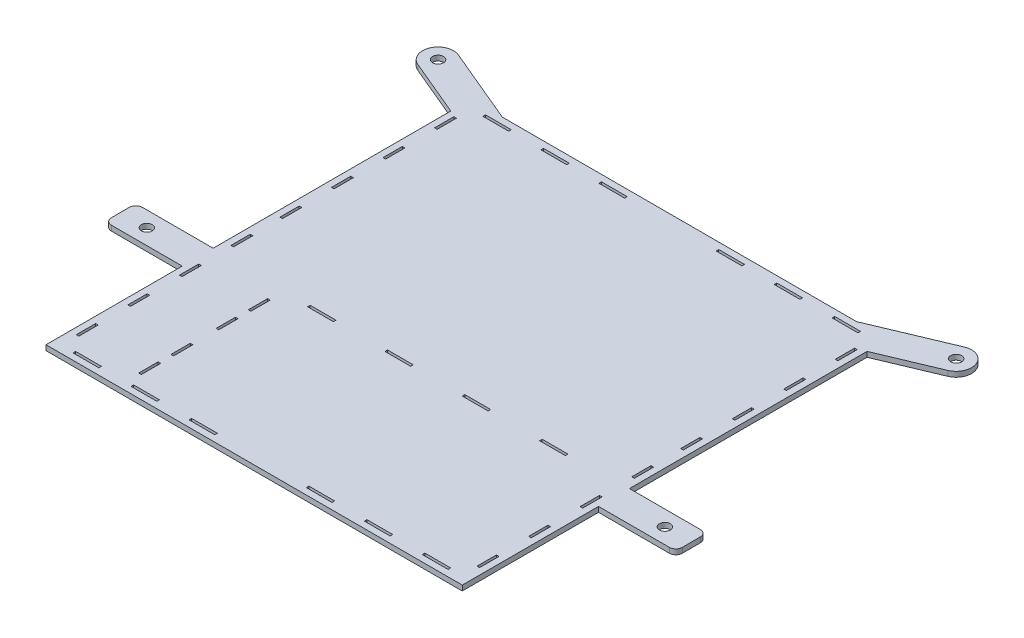
SolidWorks part; units mm, degrees
ref_plane "Front Plane" through (0, 0, 0) normal (0, 0, 1) x (1, 0, 0)
ref_plane "Top Plane" through (0, 0, 0) normal (0, 1, 0) x (1, 0, 0)
ref_plane "Right Plane" through (0, 0, 0) normal (1, 0, 0) x (0, 0, -1)
sketch "Sketch1" plane through (0, 0, 0) normal (0, 1, 0) x (1, 0, 0)
  line L0 (154.5, 106.5) -> (156.5, 106.5)
  line L1 (-161.5, -165) -> (161.5, -165)
  line L2 (-161.5, -165) -> (-161.5, -59.29)
  line L3 (-137.4311, 165) -> (137.4311, 165)
  line L4 (161.5, -165) -> (161.5, -59.29)
  line L5 (-161.5, -165) -> (161.5, 165) construction
  line L6 (-161.5, 165) -> (161.5, -165) construction
  line L7 (-155.5, -159) -> (155.5, -159) construction
  line L8 (-155.5, -159) -> (-155.5, 159) construction
  line L9 (-155.5, 159) -> (155.5, 159) construction
  line L10 (155.5, -159) -> (155.5, 159) construction
  line L11 (-155.5, -159) -> (155.5, 159) construction
  line L12 (-155.5, 159) -> (155.5, -159) construction
  line L13 (154.5, 146.5) -> (156.5, 146.5)
  line L14 (154.5, 146.5) -> (154.5, 131.5)
  line L15 (154.5, 131.5) -> (156.5, 131.5)
  line L16 (156.5, 146.5) -> (156.5, 131.5)
  line L17 (154.5, 146.5) -> (156.5, 131.5) construction
  line L18 (154.5, 131.5) -> (156.5, 146.5) construction
  line L19 (154.5, 106.5) -> (154.5, 91.5)
  line L20 (156.5, 106.5) -> (156.5, 91.5)
  line L21 (154.5, 91.5) -> (156.5, 91.5)
  line L22 (154.5, 106.5) -> (156.5, 91.5) construction
  line L23 (154.5, 91.5) -> (156.5, 106.5) construction
  line L24 (154.5, 66.5) -> (156.5, 66.5)
  line L25 (154.5, 66.5) -> (154.5, 51.5)
  line L26 (156.5, 66.5) -> (156.5, 51.5)
  line L27 (154.5, 51.5) -> (156.5, 51.5)
  line L28 (154.5, 66.5) -> (156.5, 51.5) construction
  line L29 (154.5, 51.5) -> (156.5, 66.5) construction
  line L30 (154.5, 26.5) -> (156.5, 26.5)
  line L31 (154.5, 26.5) -> (154.5, 11.5)
  line L32 (156.5, 26.5) -> (156.5, 11.5)
  line L33 (154.5, 11.5) -> (156.5, 11.5)
  line L34 (154.5, 26.5) -> (156.5, 11.5) construction
  line L35 (154.5, 11.5) -> (156.5, 26.5) construction
  line L36 (100.5, 158) -> (100.5, 160)
  line L37 (145.5, 158) -> (125.5, 158)
  line L38 (145.5, 158) -> (145.5, 160)
  line L39 (145.5, 160) -> (125.5, 160)
  line L40 (125.5, 158) -> (125.5, 160)
  line L41 (145.5, 158) -> (125.5, 160) construction
  line L42 (145.5, 160) -> (125.5, 158) construction
  line L43 (100.5, 158) -> (80.5, 158)
  line L44 (80.5, 158) -> (80.5, 160)
  line L45 (100.5, 160) -> (80.5, 160)
  line L46 (100.5, 160) -> (80.5, 158) construction
  line L47 (100.5, 158) -> (80.5, 160) construction
  line L48 (55.5, 158) -> (55.5, 160)
  line L49 (55.5, 158) -> (35.5, 158)
  line L50 (35.5, 158) -> (35.5, 160)
  line L51 (55.5, 160) -> (35.5, 160)
  line L52 (55.5, 160) -> (35.5, 158) construction
  line L53 (55.5, 158) -> (35.5, 160) construction
  line L54 (0, -55) -> (0, 55) construction
  line L55 (-55.5, 160) -> (-35.5, 158) construction
  line L56 (-55.5, 158) -> (-35.5, 160) construction
  line L57 (-55.5, 158) -> (-35.5, 158)
  line L58 (-35.5, 158) -> (-35.5, 160)
  line L59 (-55.5, 160) -> (-35.5, 160)
  line L60 (-55.5, 158) -> (-55.5, 160)
  line L61 (-145.5, 158) -> (-125.5, 160) construction
  line L62 (-145.5, 160) -> (-125.5, 158) construction
  line L63 (-145.5, 160) -> (-125.5, 160)
  line L64 (-125.5, 158) -> (-125.5, 160)
  line L65 (-145.5, 158) -> (-125.5, 158)
  line L66 (-145.5, 158) -> (-145.5, 160)
  line L67 (-100.5, 158) -> (-80.5, 160) construction
  line L68 (-100.5, 160) -> (-80.5, 158) construction
  line L69 (-100.5, 158) -> (-80.5, 158)
  line L70 (-80.5, 158) -> (-80.5, 160)
  line L71 (-100.5, 160) -> (-80.5, 160)
  line L72 (-100.5, 158) -> (-100.5, 160)
  line L73 (-154.5, 66.5) -> (-156.5, 51.5) construction
  line L74 (-154.5, 51.5) -> (-156.5, 66.5) construction
  line L75 (-154.5, 66.5) -> (-154.5, 51.5)
  line L76 (-154.5, 51.5) -> (-156.5, 51.5)
  line L77 (-156.5, 66.5) -> (-156.5, 51.5)
  line L78 (-154.5, 66.5) -> (-156.5, 66.5)
  line L79 (-154.5, 11.5) -> (-156.5, 26.5) construction
  line L80 (-154.5, 26.5) -> (-156.5, 11.5) construction
  line L81 (-154.5, 26.5) -> (-154.5, 11.5)
  line L82 (-154.5, 11.5) -> (-156.5, 11.5)
  line L83 (-156.5, 26.5) -> (-156.5, 11.5)
  line L84 (-154.5, 26.5) -> (-156.5, 26.5)
  line L85 (-154.5, 106.5) -> (-154.5, 91.5)
  line L86 (-154.5, 91.5) -> (-156.5, 91.5)
  line L87 (-156.5, 106.5) -> (-156.5, 91.5)
  line L88 (-154.5, 106.5) -> (-156.5, 106.5)
  line L89 (-154.5, 106.5) -> (-156.5, 91.5) construction
  line L90 (-154.5, 91.5) -> (-156.5, 106.5) construction
  line L91 (-154.5, 131.5) -> (-156.5, 146.5) construction
  line L92 (-154.5, 146.5) -> (-156.5, 131.5) construction
  line L93 (-154.5, 131.5) -> (-156.5, 131.5)
  line L94 (-156.5, 146.5) -> (-156.5, 131.5)
  line L95 (-154.5, 146.5) -> (-156.5, 146.5)
  line L96 (-154.5, 146.5) -> (-154.5, 131.5)
  line L97 (-156.5, -106.5) -> (-156.5, -91.5)
  line L98 (-145.5, -160) -> (-125.5, -160)
  line L99 (-145.5, -160) -> (-145.5, -158)
  line L100 (-145.5, -158) -> (-125.5, -158)
  line L101 (-125.5, -160) -> (-125.5, -158)
  line L102 (-145.5, -160) -> (-125.5, -158) construction
  line L103 (-145.5, -158) -> (-125.5, -160) construction
  line L104 (-156.5, -146.5) -> (-154.5, -146.5)
  line L105 (-156.5, -146.5) -> (-156.5, -131.5)
  line L106 (-156.5, -131.5) -> (-154.5, -131.5)
  line L107 (-154.5, -146.5) -> (-154.5, -131.5)
  line L108 (-156.5, -146.5) -> (-154.5, -131.5) construction
  line L109 (-156.5, -131.5) -> (-154.5, -146.5) construction
  line L110 (-156.5, -106.5) -> (-154.5, -106.5)
  line L111 (-154.5, -106.5) -> (-154.5, -91.5)
  line L112 (-156.5, -91.5) -> (-154.5, -91.5)
  line L113 (-156.5, -106.5) -> (-154.5, -91.5) construction
  line L114 (-156.5, -91.5) -> (-154.5, -106.5) construction
  line L115 (-156.5, -66.5) -> (-156.5, -51.5)
  line L116 (-156.5, -66.5) -> (-154.5, -66.5)
  line L117 (-154.5, -66.5) -> (-154.5, -51.5)
  line L118 (-156.5, -51.5) -> (-154.5, -51.5)
  line L119 (-156.5, -66.5) -> (-154.5, -51.5) construction
  line L120 (-156.5, -51.5) -> (-154.5, -66.5) construction
  line L121 (-156.5, -26.5) -> (-156.5, -11.5)
  line L122 (-156.5, -26.5) -> (-154.5, -26.5)
  line L123 (-154.5, -26.5) -> (-154.5, -11.5)
  line L124 (-156.5, -11.5) -> (-154.5, -11.5)
  line L125 (-156.5, -26.5) -> (-154.5, -11.5) construction
  line L126 (-156.5, -11.5) -> (-154.5, -26.5) construction
  line L127 (-100.5, -160) -> (-80.5, -158) construction
  line L128 (-100.5, -158) -> (-80.5, -160) construction
  line L129 (-100.5, -160) -> (-100.5, -158)
  line L130 (-100.5, -160) -> (-80.5, -160)
  line L131 (-80.5, -160) -> (-80.5, -158)
  line L132 (-100.5, -158) -> (-80.5, -158)
  line L133 (-55.5, -160) -> (-35.5, -158) construction
  line L134 (-55.5, -158) -> (-35.5, -160) construction
  line L135 (-55.5, -160) -> (-55.5, -158)
  line L136 (-55.5, -160) -> (-35.5, -160)
  line L137 (-35.5, -160) -> (-35.5, -158)
  line L138 (-55.5, -158) -> (-35.5, -158)
  line L139 (156.5, -11.5) -> (154.5, -26.5) construction
  line L140 (156.5, -26.5) -> (154.5, -11.5) construction
  line L141 (156.5, -26.5) -> (154.5, -26.5)
  line L142 (154.5, -26.5) -> (154.5, -11.5)
  line L143 (156.5, -11.5) -> (154.5, -11.5)
  line L144 (156.5, -26.5) -> (156.5, -11.5)
  line L145 (156.5, -66.5) -> (154.5, -51.5) construction
  line L146 (156.5, -51.5) -> (154.5, -66.5) construction
  line L147 (156.5, -66.5) -> (154.5, -66.5)
  line L148 (154.5, -66.5) -> (154.5, -51.5)
  line L149 (156.5, -51.5) -> (154.5, -51.5)
  line L150 (156.5, -66.5) -> (156.5, -51.5)
  line L151 (156.5, -106.5) -> (154.5, -91.5) construction
  line L152 (156.5, -91.5) -> (154.5, -106.5) construction
  line L153 (156.5, -106.5) -> (154.5, -106.5)
  line L154 (154.5, -106.5) -> (154.5, -91.5)
  line L155 (156.5, -91.5) -> (154.5, -91.5)
  line L156 (156.5, -106.5) -> (156.5, -91.5)
  line L157 (156.5, -131.5) -> (154.5, -146.5) construction
  line L158 (156.5, -146.5) -> (154.5, -131.5) construction
  line L159 (156.5, -131.5) -> (154.5, -131.5)
  line L160 (154.5, -146.5) -> (154.5, -131.5)
  line L161 (156.5, -146.5) -> (154.5, -146.5)
  line L162 (156.5, -146.5) -> (156.5, -131.5)
  line L163 (145.5, -160) -> (125.5, -158) construction
  line L164 (145.5, -158) -> (125.5, -160) construction
  line L165 (145.5, -158) -> (125.5, -158)
  line L166 (125.5, -160) -> (125.5, -158)
  line L167 (145.5, -160) -> (125.5, -160)
  line L168 (145.5, -160) -> (145.5, -158)
  line L169 (100.5, -158) -> (80.5, -160) construction
  line L170 (100.5, -160) -> (80.5, -158) construction
  line L171 (100.5, -160) -> (80.5, -160)
  line L172 (80.5, -160) -> (80.5, -158)
  line L173 (100.5, -158) -> (80.5, -158)
  line L174 (100.5, -160) -> (100.5, -158)
  line L175 (55.5, -160) -> (35.5, -158) construction
  line L176 (55.5, -158) -> (35.5, -160) construction
  line L177 (55.5, -160) -> (35.5, -160)
  line L178 (35.5, -160) -> (35.5, -158)
  line L179 (55.5, -158) -> (35.5, -158)
  line L180 (55.5, -160) -> (55.5, -158)
  line L181 (-161.5, -47.29) -> (-221.5, -47.29) construction
  line L182 (-156.5, 160) -> (-145.5, 160) construction
  line L183 (-156.5, -26.5) -> (-156.5, -51.5) construction
  line L184 (-156.5, 160) -> (-156.5, 146.5) construction
  line L185 (-161.5, -35.29) -> (-216.5, -35.29)
  line L186 (-161.5, -59.29) -> (-216.5, -59.29)
  line L187 (-221.5, -40.29) -> (-221.5, -47.29)
  line L188 (-221.5, -47.29) -> (-221.5, -54.29)
  line L189 (-148.3546, -35.29) -> (-221.5, -35.29) construction
  line L190 (-148.3546, -47.29) -> (-221.5, -47.29) construction
  line L191 (-148.3546, -59.29) -> (-221.5, -59.29) construction
  line L192 (-161.5, -35.29) -> (-161.5, 149.0847)
  line L193 (-161.5, -35.29) -> (-161.5, -59.29) construction
  line L194 (161.5, -35.29) -> (216.5, -35.29)
  line L195 (221.5, -40.29) -> (221.5, -47.29)
  line L196 (221.5, -47.29) -> (221.5, -54.29)
  line L197 (161.5, -59.29) -> (216.5, -59.29)
  line L198 (161.5, -35.29) -> (161.5, 149.0847)
  line L199 (-156.5, 160) -> (-201, 178.71) construction
  line L200 (-137.4311, 165) -> (-196.349, 189.772)
  line L201 (-161.5, 149.0847) -> (-205.651, 167.648)
  line L202 (-151.849, 171.062) -> (-196.349, 189.772) construction
  line L203 (-161.151, 148.938) -> (-205.651, 167.648) construction
  line L204 (-161.5, 149.0847) -> (-161.5, 165) construction
  line L205 (-161.5, 165) -> (-137.4311, 165) construction
  line L206 (145.5, 160) -> (156.5, 160) construction
  line L207 (156.5, 160) -> (156.5, 146.5) construction
  line L208 (156.5, 160) -> (201, 178.71) construction
  line L209 (161.5, 149.0847) -> (205.651, 167.648)
  line L210 (137.4311, 165) -> (196.349, 189.772)
  line L211 (151.849, 171.062) -> (196.349, 189.772) construction
  line L212 (161.151, 148.938) -> (205.651, 167.648) construction
  line L213 (137.4311, 165) -> (161.5, 165) construction
  line L214 (161.5, 165) -> (161.5, 149.0847) construction
  line L215 (139.5, -53) -> (-85.5, -53) construction
  line L216 (94.5, -38) -> (114.5, -38)
  line L217 (94.5, -38) -> (94.5, -36)
  line L218 (94.5, -36) -> (114.5, -36)
  line L219 (114.5, -38) -> (114.5, -36)
  line L220 (154.5, 158) -> (154.5, -158) construction
  line L221 (34.5, -38) -> (34.5, -36)
  line L222 (34.5, -38) -> (54.5, -38)
  line L223 (54.5, -38) -> (54.5, -36)
  line L224 (34.5, -36) -> (54.5, -36)
  line L225 (-25.5, -38) -> (-25.5, -36)
  line L226 (-25.5, -38) -> (-5.5, -38)
  line L227 (-5.5, -38) -> (-5.5, -36)
  line L228 (-25.5, -36) -> (-5.5, -36)
  line L229 (-85.5, -38) -> (-85.5, -36)
  line L230 (-85.5, -38) -> (-65.5, -38)
  line L231 (-65.5, -38) -> (-65.5, -36)
  line L232 (-85.5, -36) -> (-65.5, -36)
  line L233 (-106.5, -73) -> (-106.5, -88)
  line L238 (-106.5, -88) -> (-104.5, -88)
  line L239 (156.5, -158) -> (-156.5, -158) construction
  line L240 (-106.5, -133) -> (-104.5, -133)
  line L241 (-106.5, -133) -> (-106.5, -148)
  line L242 (-106.5, -148) -> (-104.5, -148)
  line L243 (-104.5, -133) -> (-104.5, -148)
  line L244 (-106.5, -108) -> (-106.5, -123)
  line L245 (-106.5, -108) -> (-104.5, -108)
  line L246 (-104.5, -108) -> (-104.5, -123)
  line L247 (-106.5, -123) -> (-104.5, -123)
  line L248 (-104.5, -73) -> (-104.5, -88)
  line L249 (-106.5, -73) -> (-104.5, -73)
  line L250 (-106.5, -48) -> (-106.5, -63)
  line L251 (-106.5, -63) -> (-104.5, -63)
  line L252 (-104.5, -48) -> (-104.5, -63)
  line L253 (-106.5, -48) -> (-104.5, -48)
  circle A0 centre (-201, -47.29) radius 4.25
  arc A1 (-216.5, -59.29) -> (-221.5, -54.29) centre (-216.5, -54.29) cw
  arc A2 (-221.5, -40.29) -> (-216.5, -35.29) centre (-216.5, -40.29) cw
  circle A3 centre (201, -47.29) radius 4.25
  arc A4 (221.5, -40.29) -> (216.5, -35.29) centre (216.5, -40.29) ccw
  arc A5 (216.5, -59.29) -> (221.5, -54.29) centre (216.5, -54.29) ccw
  circle A6 centre (-201, 178.71) radius 4.25
  arc A7 (-205.651, 167.648) -> (-196.349, 189.772) centre (-201, 178.71) cw
  arc A8 (196.349, 189.772) -> (205.651, 167.648) centre (201, 178.71) cw
  circle A9 centre (201, 178.71) radius 4.25
  point P0 (0, 0)
  point P6 (0, 0)
  point P11 (155.5, 139)
  point P16 (155.5, 106.5)
  point P17 (135.5, 159)
  point P72 (-135.5, -159)
  point P77 (-155.5, -139)
  point P187 (94.5, -37)
  dimension "D29" = 8.5
  dimension "D31" = 5
  dimension "D34" = 8.5
  dimension "D41" = 8.5
  dimension "D1" = 323
  dimension "D2" = 330
  dimension "D3" = 311
  dimension "D4" = 318
  dimension "D5" = 2
  dimension "D6" = 15
  dimension "D7" = 20
  dimension "D9" = 25
  dimension "D10" = 20
  dimension "D11" = 20
  dimension "D12" = 2
  dimension "D14" = 25
  dimension "D15" = 2
  dimension "D16" = 2
  dimension "D17" = 15
  dimension "D18" = 20
  dimension "D19" = 20
  dimension "D20" = 20
  dimension "D22" = 25
  dimension "D24" = 25
  dimension "D25" = 207.29
  dimension "D28" = 60
  dimension "D30" = 39.5
  dimension "D32" = 44.5
  dimension "D33" = 18.71
  dimension "D37" = 18.71
  dimension "D38" = 44.5
  dimension "D39" = 12
  dimension "D42" = 15
  dimension "D43" = 2
  dimension "D44" = 20
  dimension "D45" = 40
  dimension "D47" = 40
  dimension "D48" = 2
  dimension "D49" = 15
  dimension "D50" = 10
  dimension "D52" = 10
  dimension "D53" = 48
  dimension "D56" = 10
  dimension "D57" = 20
  dimension "D26" = 12
  dimension "D27" = 12
  dimension "D35" = 12
  dimension "D36" = 12
  dimension "D40" = 12
  dimension "D8" = 4
  dimension "D13" = 3
  dimension "D21" = 4
  dimension "D23" = 3
  dimension "D46" = 4
  dimension "D51" = 2
  dimension "D54" = 2
  dimension "D55" = 2
extrude "Boss-Extrude1" add sketch "Sketch1" along normal blind 4
